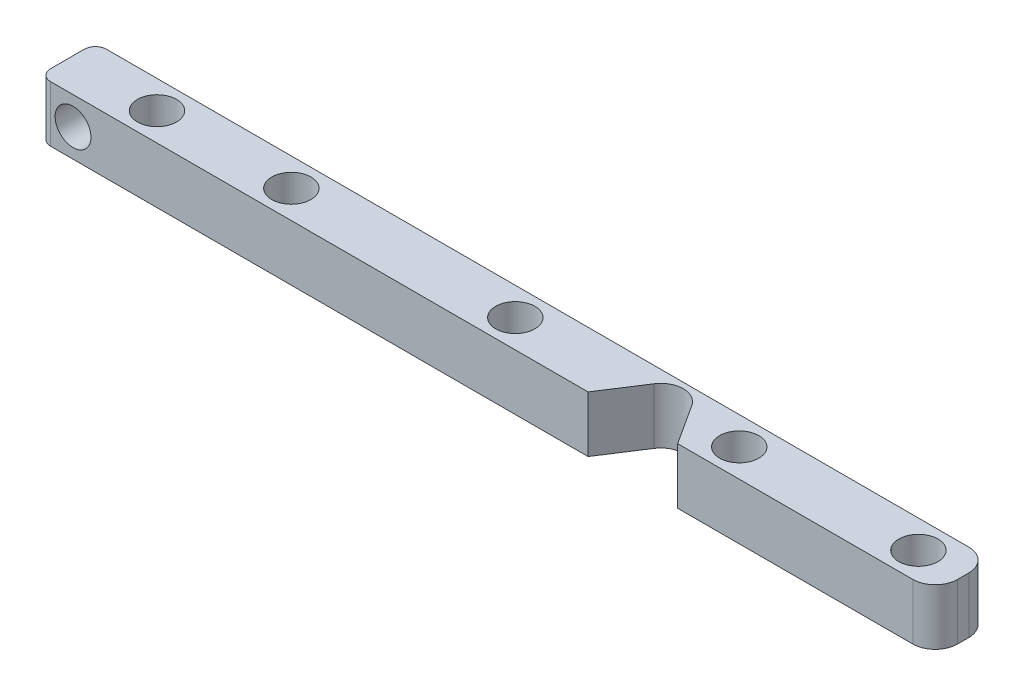
SolidWorks part; units mm, degrees
ref_plane "Front Plane" through (0, 0, 0) normal (0, 0, 1) x (1, 0, 0)
ref_plane "Top Plane" through (0, 0, 0) normal (0, 1, 0) x (1, 0, 0)
ref_plane "Right Plane" through (0, 0, 0) normal (1, 0, 0) x (0, 0, -1)
sketch "Sketch1" plane through (0, 0, 0) normal (0, 1, 0) x (1, 0, 0)
  line L1 (-50.8, 3.175) -> (50.8, 3.175)
  line L2 (-50.8, 3.175) -> (-50.8, -3.175)
  line L3 (-50.8, -3.175) -> (50.8, -3.175)
  line L4 (50.8, 3.175) -> (50.8, -3.175)
  line L5 (-50.8, 3.175) -> (50.8, -3.175) construction
  line L6 (-50.8, -3.175) -> (50.8, 3.175) construction
  point P0 (0, 0)
  dimension "D1" = 6.35
  dimension "D2" = 101.6
extrude "Boss-Extrude1" add sketch "Sketch1" along normal blind 6.35 contours L4 L1 L2 L3
fillet "Fillet1" radius 2.54 2 edges at (50.8, 3.175, -3.175) (50.8, 3.175, 3.175)
fillet "Fillet2" radius 1.27 2 edges at (-50.8, 3.175, -3.175) (-50.8, 3.175, 3.175)
sketch "Sketch2" plane through (0, 6.35, 0) normal (0, 1, 0) x (1, 0, 0)
  line L0 (-50.8, 0) -> (50.8, 0) construction
  line L1 (-50.8, 1.905) -> (-50.8, -1.905) construction
  line L2 (50.8, 0.635) -> (50.8, -0.635) construction
  circle A0 centre (-40.64, 0) radius 2.2225
  circle A1 centre (45.72, 0) radius 2.2225
  circle A2 centre (25.4, 0) radius 2.2225
  circle A3 centre (-25.4, 0) radius 2.2225
  circle A4 centre (0, 0) radius 2.2225
  dimension "D1" = 4.445
  dimension "D2" = 5.08
  dimension "D3" = 25.4
  dimension "D4" = 25.4
  dimension "D5" = 40.64
extrude "Cut-Extrude1" cut sketch "Sketch2" against normal up to next contours A0 | A3 | A4 | A2 | A1
sketch "Sketch3" plane through (0, 0, 3.175) normal (0, 0, 1) x (1, 0, 0)
  line L1 (-49.53, 3.175) -> (-46.99, 3.175) construction
  line L2 (-49.53, 6.35) -> (-49.53, 0) construction
  circle A0 centre (-46.99, 3.175) radius 2.032
  point P2 (0, 0)
  point P5 (0, 0)
  dimension "D1" = 2.54
  dimension "D2" = 4.064
extrude "Cut-Extrude2" cut sketch "Sketch3" against normal up to next
sketch "Sketch4" plane through (0, 6.35, 0) normal (0, 1, 0) x (1, 0, 0)
  line L0 (14.3775, 1.3799) -> (11.43, -3.175)
  line L1 (-49.53, -3.175) -> (48.26, -3.175) construction
  line L2 (18.6425, 1.3799) -> (21.59, -3.175)
  circle A0 centre (16.51, 0) radius 2.54
  circle A1 centre (45.72, 0) radius 2.2225 construction
  circle A2 centre (45.72, 0) radius 2.2225
  point P7 (0, 0)
  point P12 (0, 0)
  line M12 (-49.53, -3.175) -> (48.26, -3.175)
  dimension "D1" = 5.08
  dimension "D2" = 29.21
  dimension "D3" = 5.08
extrude "Cut-Extrude3" cut sketch "Sketch4" against normal up to next contours A0 L0 L2 M12
